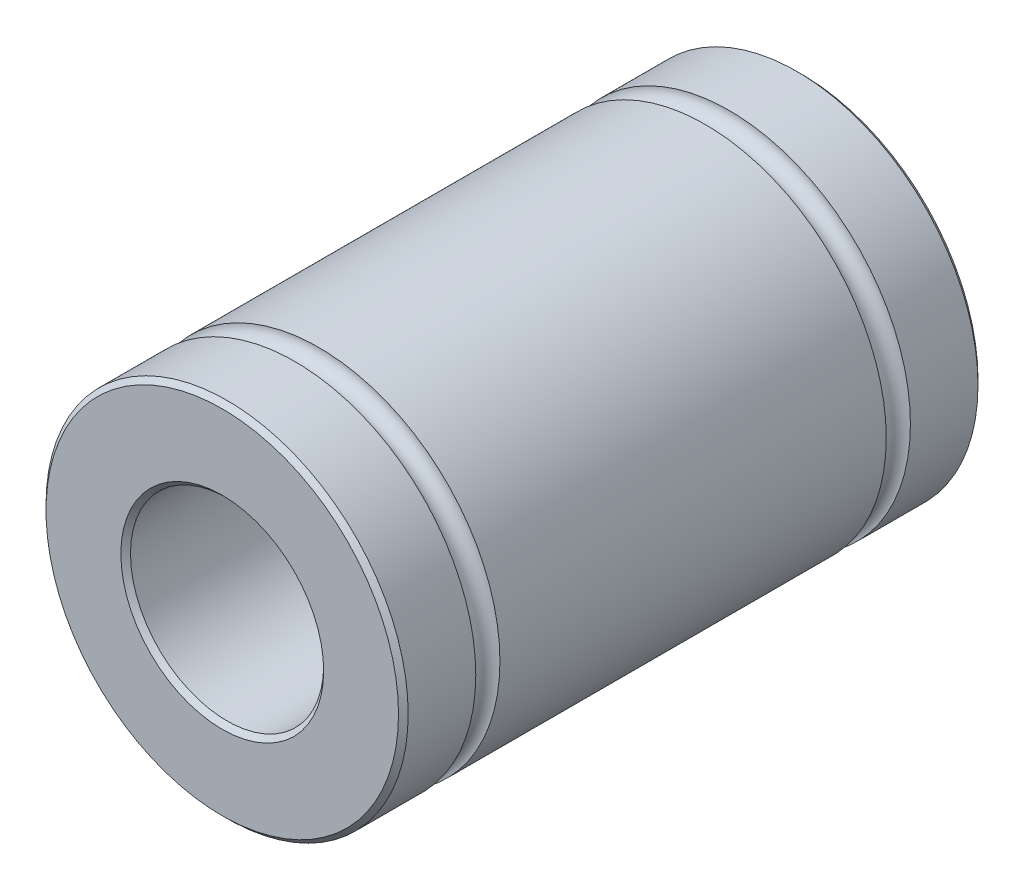
SolidWorks part; units mm, degrees
ref_plane "Plan de face" through (0, 0, 0) normal (0, 0, 1) x (1, 0, 0)
ref_plane "Plan de dessus" through (0, 0, 0) normal (0, 1, 0) x (1, 0, 0)
ref_plane "Plan de droite" through (0, 0, 0) normal (1, 0, 0) x (0, 0, -1)
ref_axis "Axe1" through (0, 0, 55) along (0, 0, -1)
sketch "Esquisse1" plane through (0, 0, 0) normal (0, 0, 1) x (1, 0, 0)
  circle A0 centre (0, 0) radius 7.5
  circle A1 centre (0, 0) radius 4
  dimension "D1" = 15
  dimension "D2" = 8
extrude "Boss.-Extru.1" add sketch "Esquisse1" along normal mid plane 24
chamfer "Chanfrein1" distance 0.2 angle 45 4 edges at (4, 0, -12) (7.5, 0, -12) (4, 0, 12) (7.5, 0, 12)
sketch "Esquisse2" plane through (0, 0, 0) normal (1, 0, 0) x (0, 0, -1)
  line L0 (11.8, 7.5) -> (-11.8, 7.5) construction
  line L1 (-12, 7.3) -> (-12, -7.3) construction
  line L2 (-9, 7.5) -> (-8, 7.5)
  line L3 (-55, 0) -> (55, 0) construction
  arc A0 (-8, 7.5) -> (-9, 7.5) centre (-8.5, 7.5) cw
  point P7 (-8.5, 7)
  dimension "D1" = 3.5
  dimension "D2" = 1
  dimension "D3" = 7
revolve "Enlèvement de matière-Révolution1" cut sketch "Esquisse2" angle 360 about axis through (0, 0, 55) along (0, 0, -1)
mirror "Symétrie1" about plane through (0, 0, 0) normal (0, 0, 1) of "Enlèvement de matière-Révolution1"
